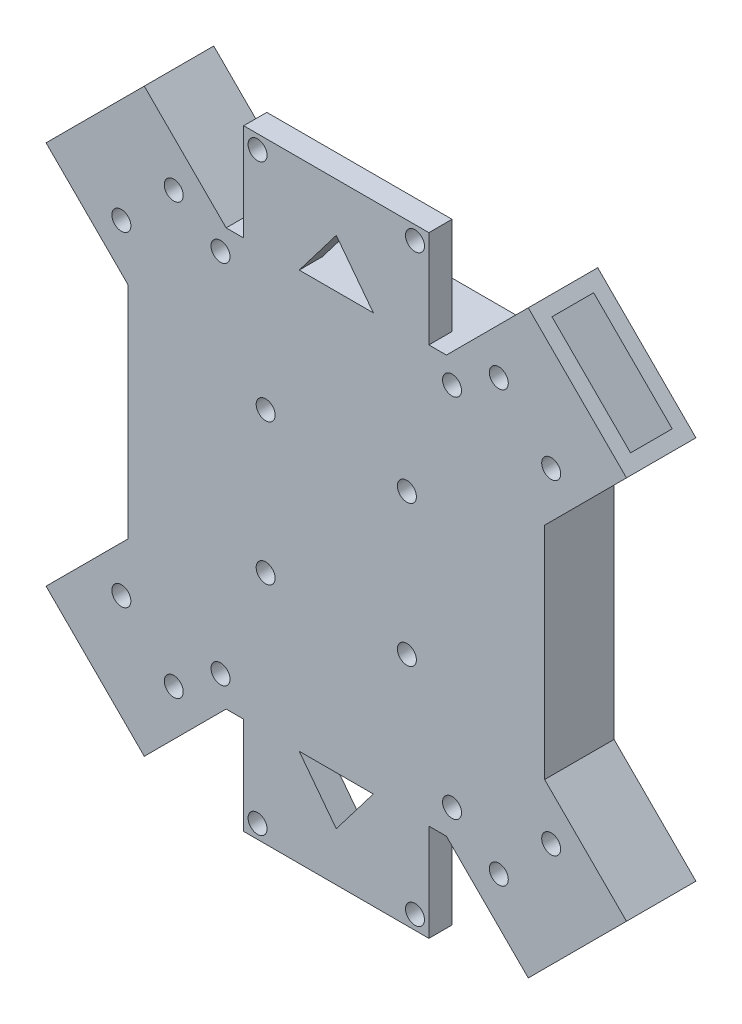
SolidWorks part; units mm, degrees
ref_plane "Front Plane" through (0, 0, 0) normal (1, 0, 0) x (0, 1, 0)
ref_plane "Top Plane" through (0, 0, 0) normal (0, 0, 1) x (0, 1, 0)
ref_plane "Right Plane" through (0, 0, 0) normal (0, 1, 0) x (-1, 0, 0)
sketch "Sketch1" plane through (0, 0, 0) normal (0, 0, 1) x (0, 1, 0)
  line L0 (-1.3696, -65.0647) -> (-1.3696, 24.9353) construction
  line L1 (-46.3696, 24.9353) -> (43.6304, 24.9353)
  line L2 (-46.3696, 24.9353) -> (-46.3696, -65.0647)
  line L3 (-46.3696, -65.0647) -> (43.6304, -65.0647)
  line L4 (43.6304, 24.9353) -> (43.6304, -65.0647)
  line L5 (-46.3696, 9.9353) -> (43.6304, 9.9353)
  line L6 (-46.3696, 9.9353) -> (-46.3696, -50.0647)
  line L7 (-46.3696, -50.0647) -> (43.6304, -50.0647)
  line L8 (43.6304, 9.9353) -> (43.6304, -50.0647)
  line L9 (-46.3696, -20.0647) -> (43.6304, -20.0647) construction
  line L10 (-26.3603, 9.9353) -> (-26.3603, 24.9353) construction
  line L11 (-20.3171, -50.0647) -> (-20.3171, -65.0647) construction
  line L12 (-1.3696, -4.8147) -> (-1.3696, -35.3147) construction
  line L13 (-16.6196, -4.8147) -> (13.8804, -4.8147)
  line L14 (-16.6196, -4.8147) -> (-16.6196, -35.3147)
  line L15 (-16.6196, -35.3147) -> (13.8804, -35.3147)
  line L16 (13.8804, -4.8147) -> (13.8804, -35.3147)
  line L17 (-16.6196, -20.0647) -> (13.8804, -20.0647) construction
  line L18 (-6.3696, -4.8147) -> (-6.3696, 1.1853) construction
  line L19 (-6.3696, 1.1853) -> (3.6304, 1.1853) construction
  line L20 (3.6304, 1.1853) -> (3.6304, -4.8147) construction
  circle A0 centre (-40.3696, 4.9353) radius 2.05
  circle A1 centre (-40.3696, -45.0647) radius 2.05
  circle A2 centre (38.6304, 4.9353) radius 2.05
  circle A3 centre (38.6304, -45.0647) radius 2.05
  circle A4 centre (13.8804, -4.8147) radius 2.05
  circle A5 centre (-16.6196, -4.8147) radius 2.05
  circle A6 centre (13.8804, -35.3147) radius 2.05
  circle A7 centre (-16.6196, -35.3147) radius 2.05
  point P36 (-1.3696, -20.0647)
  point P38 (-1.3696, -20.0647)
  dimension "D4" = 5
  dimension "D6" = 4.1
  dimension "D7" = 4.1
  dimension "D11" = 4.1
  dimension "D1" = 90
  dimension "D2" = 90
  dimension "D3" = 60
  dimension "D5" = 6
  dimension "D8" = 5
  dimension "D9" = 5
  dimension "D10" = 30.5
  dimension "D12" = 10
  dimension "D13" = 5
  dimension "D14" = 6
extrude "Boss-Extrude1" add sketch "Sketch1" along normal blind 15 contours L7 L2 L3 L4 | L2 L7 L4 L5 A7 L14 A5 L13 A4 L16 A6 L15 A1 A0 A2 A3 | A7 L15 A6 L16 A4 L13 A5 L14 | L2 L5 L4 L1
sketch "Sketch2" plane through (0, 0, 15) normal (0, 0, 1) x (1, 0, 0)
  line L0 (-42.613, 40.0949) -> (-21.3998, 61.3081)
  line L1 (-24.9353, 43.6304) -> (65.0647, 43.6304) construction
  line L2 (65.0647, 43.6304) -> (65.0647, -46.3696) construction
  line L3 (65.0647, -46.3696) -> (-24.9353, -46.3696) construction
  line L4 (-24.9353, -46.3696) -> (-24.9353, 43.6304) construction
  line L5 (-24.9353, -46.3696) -> (65.0647, -46.3696) construction
  line L6 (-24.9353, -46.3696) -> (-24.9353, 43.6304) construction
  line L7 (20.0647, 43.6304) -> (20.0647, -46.3696) construction
  line L8 (20.0647, -46.3696) -> (20.0647, -1.3696) construction
  line L9 (20.0647, -1.3696) -> (-24.9353, -1.3696) construction
  line L10 (-24.9353, -1.3696) -> (20.0647, -1.3696) construction
  line L11 (20.0647, -1.3696) -> (65.0647, -1.3696) construction
  line L12 (-24.9353, 43.6304) -> (20.0647, -1.3696) construction
  line L13 (-42.613, 40.0949) -> (-24.9353, 22.4172)
  line L14 (-24.9353, 22.4172) -> (-3.7221, 43.6304)
  line L15 (-3.7221, 43.6304) -> (-21.3998, 61.3081)
  line L16 (-33.7742, 31.2561) -> (-12.561, 52.4693) construction
  line L17 (-12.561, 52.4693) -> (-3.7221, 43.6304) construction
  line L18 (-33.7742, 31.2561) -> (-24.9353, 22.4172) construction
  line L19 (-29.3547, 26.8366) -> (-8.1415, 48.0499) construction
  line L20 (73.9035, 31.2561) -> (65.0647, 22.4172) construction
  line L21 (65.0647, 22.4172) -> (43.8515, 43.6304)
  line L22 (82.7423, 40.0949) -> (65.0647, 22.4172)
  line L23 (52.6903, 52.4693) -> (43.8515, 43.6304) construction
  line L24 (43.8515, 43.6304) -> (61.5291, 61.3081)
  line L25 (82.7423, 40.0949) -> (61.5291, 61.3081)
  line L26 (52.6903, -55.2084) -> (43.8515, -46.3696) construction
  line L27 (73.9035, -33.9952) -> (65.0647, -25.1564) construction
  line L28 (-33.7742, -33.9952) -> (-24.9353, -25.1564) construction
  line L29 (-12.561, -55.2084) -> (-3.7221, -46.3696) construction
  line L30 (-24.9353, -46.3696) -> (65.0647, -46.3696) construction
  line L31 (82.7423, -42.834) -> (61.5291, -64.0472)
  line L32 (43.8515, -46.3696) -> (61.5291, -64.0472)
  line L33 (82.7423, -42.834) -> (65.0647, -25.1564)
  line L34 (65.0647, -25.1564) -> (43.8515, -46.3696)
  line L35 (-3.7221, -46.3696) -> (-21.3998, -64.0472)
  line L36 (-24.9353, -25.1564) -> (-3.7221, -46.3696)
  line L37 (-42.613, -42.834) -> (-24.9353, -25.1564)
  line L38 (-42.613, -42.834) -> (-21.3998, -64.0472)
  circle A0 centre (-24.405, 31.7864) radius 2.05
  circle A1 centre (-13.0913, 43.1001) radius 2.05
  circle A2 centre (53.2206, 43.1001) radius 2.05
  circle A3 centre (64.5343, 31.7864) radius 2.05
  circle A4 centre (64.5343, -34.5255) radius 2.05
  circle A5 centre (53.2206, -45.8392) radius 2.05
  circle A6 centre (-13.0913, -45.8392) radius 2.05
  circle A7 centre (-24.405, -34.5255) radius 2.05
  line M9 (65.0647, 43.6304) -> (-24.9353, 43.6304)
  line M10 (-24.9353, 43.6304) -> (-24.9353, -46.3696)
  line M11 (-24.9353, -46.3696) -> (65.0647, -46.3696)
  line M12 (65.0647, -46.3696) -> (65.0647, 43.6304)
  dimension "D3" = 8
  dimension "D5" = 4.1
  dimension "D6" = 4.1
  dimension "D1" = 30
  dimension "D2" = 25
  dimension "D4" = 8
extrude "Boss-Extrude2" add sketch "Sketch2" against normal blind 15 contours A1 L15 L0 L13 A0 M9 M10 | A1 A0 L14 M9 M10 | A3 L22 L25 L24 A2 M12 M9 | A3 A2 L21 M12 M9 | A5 A4 L34 M11 M12 | A5 L32 L31 L33 A4 M11 M12 | A7 A6 L36 M10 M11 | A7 L37 L38 L35 A6 M10 M11
sketch "Sketch4" plane through (0, 0, 15) normal (0, 0, 1) x (1, 0, 0)
  line L0 (-42.613, 40.0949) -> (-24.9353, 22.4172) construction
  line L1 (-24.9353, 22.4172) -> (-3.7221, 43.6304) construction
  line L2 (-3.7221, 43.6304) -> (-21.3998, 61.3081) construction
  line L3 (-21.3998, 61.3081) -> (-42.613, 40.0949) construction
  line L4 (-3.7221, 43.6304) -> (-21.3998, 61.3081) construction
  line L5 (-33.7742, 31.2561) -> (-12.561, 52.4693) construction
  line L6 (-12.561, 52.4693) -> (-3.7221, 43.6304) construction
  line L7 (-33.7742, 31.2561) -> (-24.9353, 22.4172) construction
  line L8 (-31.2993, 28.7812) -> (-10.0861, 49.9944) construction
  line L9 (-32.0064, 50.7015) -> (-14.3287, 33.0238) construction
  line L10 (20.0647, 43.6304) -> (20.0647, -46.3696) construction
  line L11 (-3.7221, 43.6304) -> (43.8515, 43.6304) construction
  line L12 (-3.7221, -46.3696) -> (43.8515, -46.3696) construction
  line L13 (-24.9353, -1.3696) -> (65.0647, -1.3696) construction
  line L14 (-24.9353, -25.1564) -> (-24.9353, 22.4172) construction
  line L15 (65.0647, -25.1564) -> (65.0647, 22.4172) construction
  circle A0 centre (-26.3495, 33.7309) radius 2.05
  circle A1 centre (-15.0358, 45.0446) radius 2.05
  circle A2 centre (66.4789, 33.7309) radius 2.05
  circle A3 centre (55.1652, 45.0446) radius 2.05
  circle A4 centre (66.4789, -36.4701) radius 2.05
  circle A5 centre (55.1652, -47.7838) radius 2.05
  circle A6 centre (-15.0358, -47.7838) radius 2.05
  circle A7 centre (-26.3495, -36.4701) radius 2.05
  dimension "D1" = 25
  dimension "D3" = 16
  dimension "D4" = 4.1
  dimension "D5" = 4.1
  dimension "D2" = 30
  dimension "D6" = 8
  dimension "D7" = 9
extrude "Cut-Extrude1" cut sketch "Sketch4" against normal blind 15 contours A1 | A0 | A2 | A3 | A4 | A5 | A6 | A7
sketch "Sketch6" plane through (-41.3539, 41.3539, 0) normal (-0.7071, 0.7071, 0) x (-0.7071, -0.7071, 0)
  line L0 (1.7806, 15) -> (-28.2194, 15) construction
  line L1 (-25.2194, 12.0096) -> (-1.2194, 12.0096)
  line L2 (-25.2194, 12.0096) -> (-25.2194, 3)
  line L3 (-25.2194, 3) -> (-1.2194, 3)
  line L4 (-1.2194, 12.0096) -> (-1.2194, 3)
  line L5 (-28.2194, 0) -> (-28.2194, 15) construction
  line L6 (1.7806, 0) -> (-28.2194, 0) construction
  line L7 (1.7806, 0) -> (1.7806, 15) construction
  dimension "D1" = 2.9904
  dimension "D2" = 3
  dimension "D3" = 3
  dimension "D4" = 3
extrude "Cut-Extrude2" cut sketch "Sketch6" against normal blind 22
sketch "Sketch7" plane through (-42.7235, -42.7235, 0) normal (-0.7071, -0.7071, 0) x (0.7071, -0.7071, 0)
  line L0 (0.1563, 15) -> (30.1563, 15) construction
  line L1 (3.1563, 12) -> (27.1563, 12)
  line L2 (3.1563, 12) -> (3.1563, 3)
  line L3 (3.1563, 3) -> (27.1563, 3)
  line L4 (27.1563, 12) -> (27.1563, 3)
  line L5 (0.1563, 0) -> (30.1563, 0) construction
  line L6 (30.1563, 0) -> (30.1563, 15) construction
  line L7 (0.1563, 0) -> (0.1563, 15) construction
  dimension "D1" = 3
  dimension "D2" = 3
  dimension "D3" = 3
  dimension "D4" = 3
sketch "Sketch8" plane through (62.7882, -62.7882, 0) normal (0.7071, -0.7071, 0) x (0.7071, 0.7071, 0)
  line L0 (28.2194, 15) -> (-1.7806, 15) construction
  line L1 (1.2194, 12) -> (25.2194, 12)
  line L2 (1.2194, 12) -> (1.2194, 3)
  line L3 (1.2194, 3) -> (25.2194, 3)
  line L4 (25.2194, 12) -> (25.2194, 3)
  line L5 (28.2194, 0) -> (28.2194, 15) construction
  line L6 (28.2194, 0) -> (-1.7806, 0) construction
  line L7 (-1.7806, 0) -> (-1.7806, 15) construction
  dimension "D1" = 3
  dimension "D2" = 3
  dimension "D3" = 3
  dimension "D4" = 3
sketch "Sketch9" plane through (61.4186, 61.4186, 0) normal (0.7071, 0.7071, 0) x (-0.7071, 0.7071, 0)
  line L0 (-30.1563, 15) -> (-0.1563, 15) construction
  line L1 (-27.1563, 12) -> (-3.1563, 12)
  line L2 (-27.1563, 12) -> (-27.1563, 3)
  line L3 (-27.1563, 3) -> (-3.1563, 3)
  line L4 (-3.1563, 12) -> (-3.1563, 3)
  line L5 (-30.1563, 0) -> (-0.1563, 0) construction
  line L6 (-0.1563, 0) -> (-0.1563, 15) construction
  line L7 (-30.1563, 0) -> (-30.1563, 15) construction
  dimension "D1" = 3
  dimension "D2" = 3
  dimension "D3" = 3
  dimension "D4" = 3
extrude "Cut-Extrude3" cut sketch "Sketch9" against normal blind 22 contours L1 L4 L3 L2
extrude "Cut-Extrude4" cut sketch "Sketch7" against normal blind 22 contours L4 L3 L2 L1
extrude "Cut-Extrude5" cut sketch "Sketch8" against normal blind 22 contours L4 L3 L2 L1
sketch "Sketch10" plane through (0, 0, 15) normal (0, 0, 1) x (1, 0, 0)
  line L0 (43.8515, 43.6304) -> (43.8515, -46.3696) construction
  line L1 (0.0647, 64.6304) -> (40.0647, 64.6304)
  line L2 (0.0647, 64.6304) -> (0.0647, -67.3696)
  line L3 (0.0647, -67.3696) -> (40.0647, -67.3696)
  line L4 (40.0647, 64.6304) -> (40.0647, -67.3696)
  line L5 (-3.7221, 43.6304) -> (-3.7221, -46.3696) construction
  line L6 (-3.7221, -1.3696) -> (0.0647, -1.3696) construction
  line L7 (40.0647, -1.3696) -> (43.8515, -1.3696) construction
  line L8 (20.0647, 43.6304) -> (20.0647, 64.6304) construction
  line L9 (-3.7221, 43.6304) -> (43.8515, 43.6304) construction
  line L10 (23.5229, -67.3696) -> (23.5229, -46.3696) construction
  line L11 (-3.7221, -46.3696) -> (43.8515, -46.3696) construction
  line L12 (20.0647, 54.1304) -> (12.0647, 43.6304)
  line L13 (12.0647, 43.6304) -> (28.0647, 43.6304)
  line L14 (28.0647, 43.6304) -> (20.0647, 54.1304)
  line L15 (0.0647, -1.3696) -> (40.0647, -1.3696) construction
  line L16 (20.0647, -56.8696) -> (12.0647, -46.3696)
  line L17 (28.0647, -46.3696) -> (20.0647, -56.8696)
  circle A0 centre (3.0647, 61.6304) radius 2.05
  circle A1 centre (37.0647, 61.6304) radius 2.05
  circle A2 centre (37.0647, -64.3696) radius 2.05
  circle A3 centre (3.0647, -64.3696) radius 2.05
  point P26 (20.0647, 64.6304)
  point P27 (20.0647, 43.6304)
  point P36 (20.0647, -46.3696)
  point P41 (20.0647, -67.3696)
  line M14 (43.8515, 43.6304) -> (-3.7221, 43.6304)
  line M22 (-3.7221, -46.3696) -> (43.8515, -46.3696)
  dimension "D2" = 4.1
  dimension "D1" = 132
  dimension "D3" = 40
  dimension "D4" = 3
  dimension "D5" = 3
  dimension "D6" = 12
extrude "Boss-Extrude3" add sketch "Sketch10" against normal blind 5 contours L14 L4 L1 L2 L12 A0 A1 M14 | L17 L16 L2 L3 L4 A2 A3 M22
